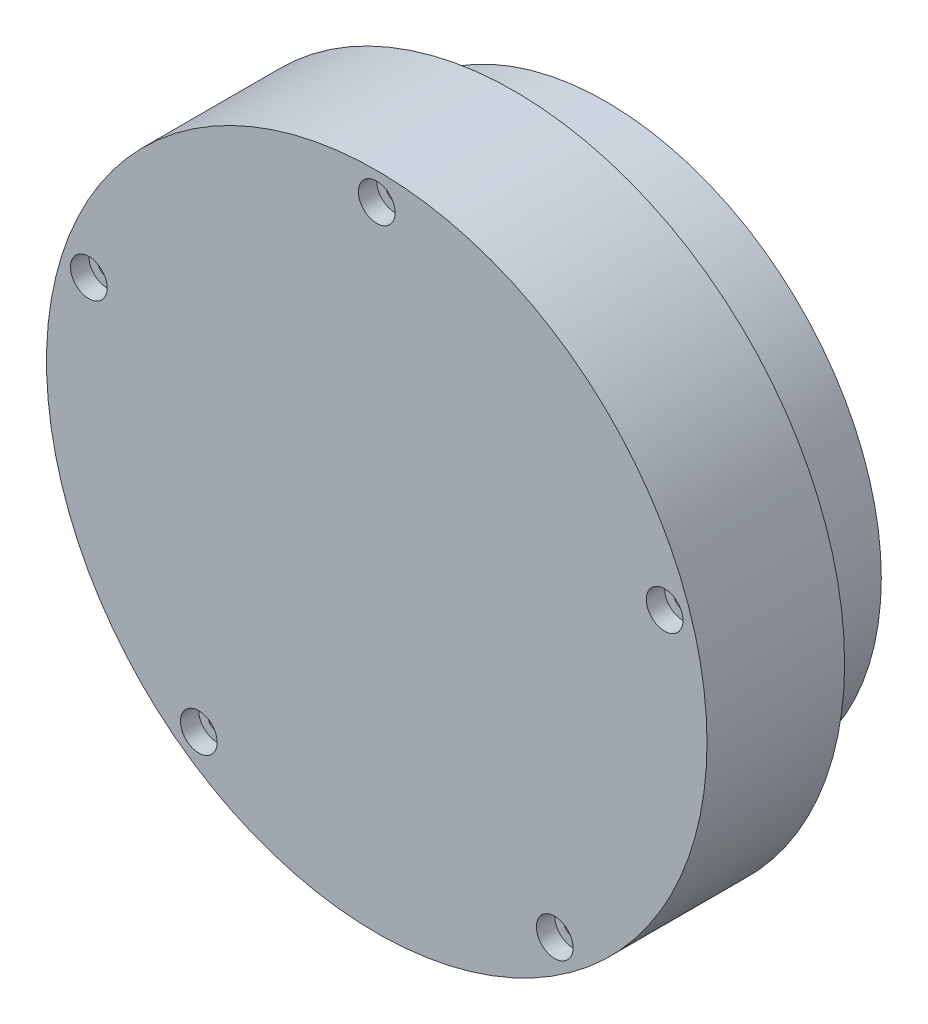
SolidWorks part; units mm, degrees
ref_plane "Front Plane" through (0, 0, 0) normal (1, 0, 0) x (0, 1, 0)
ref_plane "Top Plane" through (0, 0, 0) normal (0, 0, 1) x (0, 1, 0)
ref_plane "Right Plane" through (0, 0, 0) normal (0, 1, 0) x (-1, 0, 0)
sketch "Sketch1" plane through (0, 0, 0) normal (1, 0, 0) x (0, 1, 0)
  line L0 (0, 48.9591) -> (0, -50.2002) construction
  line L1 (0, 33.8805) -> (-45.72, 33.8805)
  line L2 (-45.72, 33.8805) -> (-45.72, 14.8305)
  line L3 (-45.72, 14.8305) -> (-38.1, 14.8305)
  line L4 (-38.1, 14.8305) -> (-38.1, 2.1305)
  line L5 (-38.1, 2.1305) -> (0, 2.1305)
  line L6 (0, 2.1305) -> (0, 33.8805)
  dimension "D1" = 38.1
  dimension "D2" = 45.72
  dimension "D3" = 12.7
  dimension "D4" = 19.05
revolve "Revolve1" add sketch "Sketch1" angle 360 about L0
sketch "Sketch2" plane through (0, 0, 33.8805) normal (0, 0, 1) x (1, 0, 0)
  line L0 (0, 45.72) -> (0, -50.6807) construction
  circle A0 centre (0, 41.91) radius 1.27
  circle A1 centre (0, 0) radius 45.72 construction
  dimension "D1" = 2.54
  dimension "D2" = 41.91
extrude "Cut-Extrude1" cut sketch "Sketch2" against normal blind 27.94
sketch "Sketch3" plane through (0, 0, 33.8805) normal (0, 0, 1) x (1, 0, 0)
  circle A0 centre (0, 41.91) radius 2.54
  dimension "D1" = 5.08
extrude "Cut-Extrude5" cut sketch "Sketch3" against normal blind 2.54
pattern_circular "CirPattern1" count 5 over 360 about axis through (0, 0, 0) along (0, 0, 1) of "Cut-Extrude5", "Cut-Extrude1"
